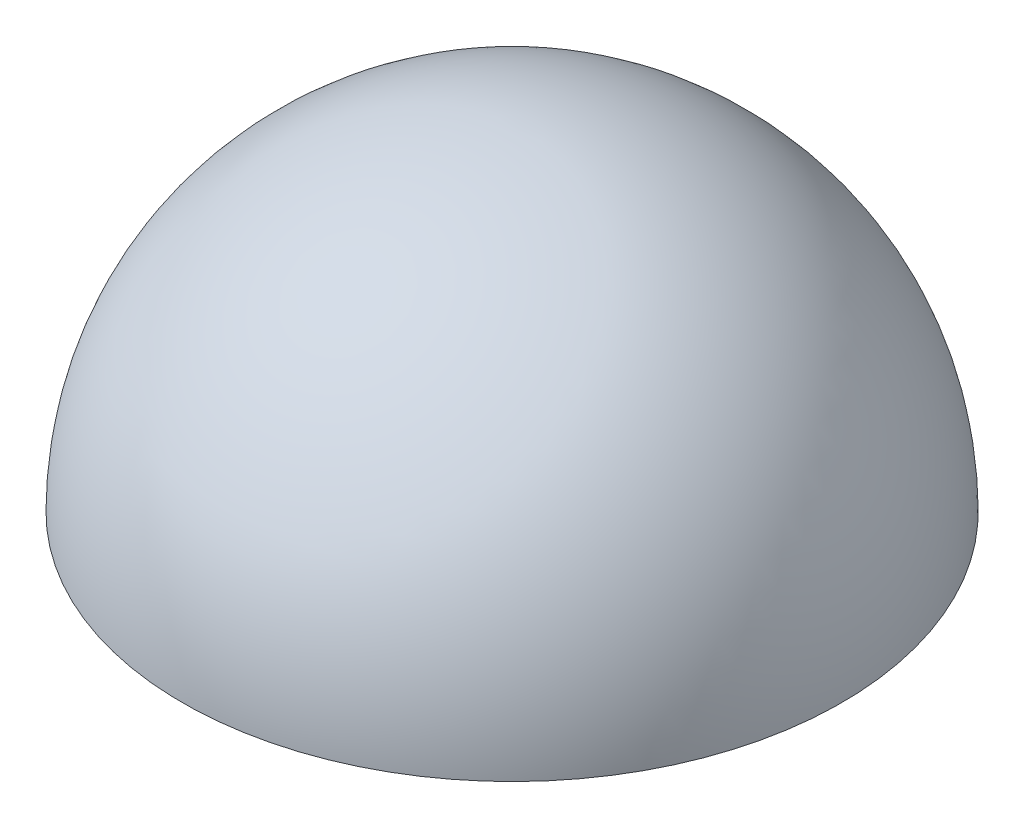
SolidWorks part; units mm, degrees
ref_plane "Front Plane" through (0, 0, 0) normal (0, 0, 1) x (1, 0, 0)
ref_plane "Top Plane" through (0, 0, 0) normal (0, 1, 0) x (1, 0, 0)
ref_plane "Right Plane" through (0, 0, 0) normal (1, 0, 0) x (0, 0, -1)
sketch "Sketch1" plane through (0, 0, 0) normal (0, 1, 0) x (1, 0, 0)
  line L0 (-0.75, 0) -> (0.75, 0)
  arc A0 (0.75, 0) -> (-0.75, 0) centre (0, 0) ccw
revolve "Revolve1" add sketch "Sketch1" angle 180 about L0
